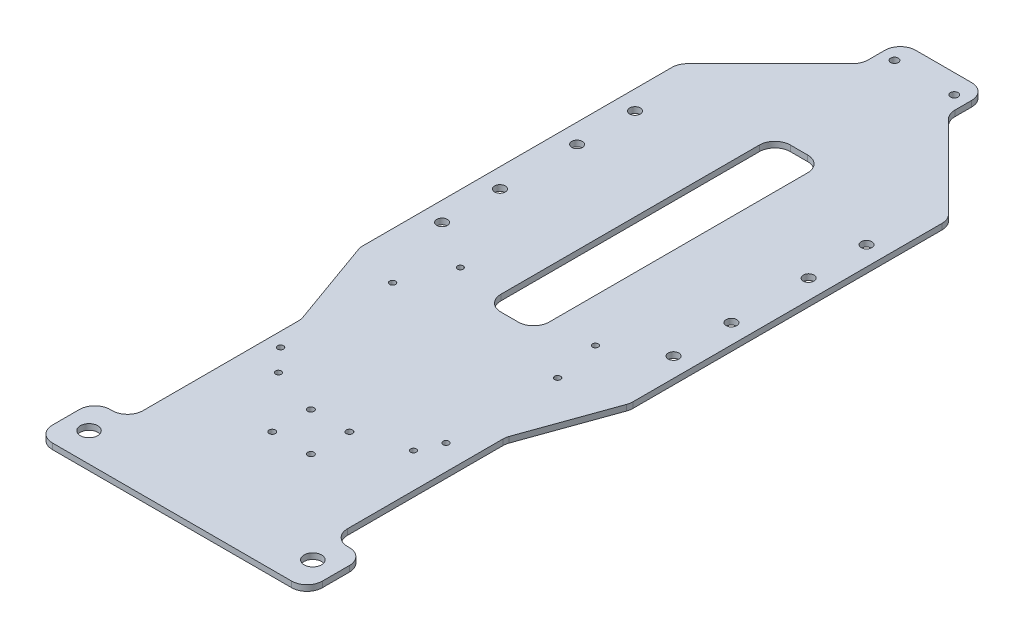
SolidWorks part; units mm, degrees
ref_plane "Front Plane" through (0, 0, 0) normal (0, 0, 1) x (1, 0, 0)
ref_plane "Top Plane" through (0, 0, 0) normal (0, 1, 0) x (1, 0, 0)
ref_plane "Right Plane" through (0, 0, 0) normal (1, 0, 0) x (0, 0, -1)
sketch "Sketch1" plane through (0, 0, 0) normal (0, 1, 0) x (1, 0, 0)
  line L0 (0, 200.8671) -> (139, 200.8671) construction
  line L1 (120.6906, 206.9991) -> (259.6906, 206.9991) construction
  line L2 (47.5, 400) -> (92.5, 400)
  line L3 (140, 332.5) -> (140, 167.5)
  line L4 (140, 167.5) -> (123, 120)
  line L6 (123, 120) -> (123, 30)
  line L7 (140, 30) -> (140, 0)
  line L8 (140, 0) -> (0, 0)
  line L9 (0, 0) -> (0, 30)
  line L10 (0, 167.5) -> (0, 332.5)
  line L12 (123, 30) -> (140, 30)
  line L13 (92.5, 400) -> (92.5, 380)
  line L14 (92.5, 380) -> (140, 332.5)
  line L15 (47.5, 400) -> (47.5, 380)
  line L16 (47.5, 380) -> (0, 332.5)
  line L17 (0, 167.5) -> (17, 120)
  line L19 (17, 120) -> (17, 30)
  line L21 (17, 30) -> (0, 30)
  line L22 (0, 332.5) -> (140, 332.5)
  dimension "D1" = 139
  dimension "D2" = 139
  dimension "D3" = 165
  dimension "D4" = 140
  dimension "D5" = 45
  dimension "D6" = 47.5
  dimension "D7" = 30
  dimension "D8" = 47.5
  dimension "D9" = 20
  dimension "D14" = 200.8671
  dimension "D16" = 206.9991
  dimension "D19" = 90
  dimension "D20" = 17
extrude "Boss-Extrude2" add sketch "Sketch1" along normal blind 3 contours L10 L16 L15 L2 L13 L14 L3 L4 L6 L12 L7 L8 L9 L21 L19 L17
sketch "Sketch2" plane through (0, 3, 0) normal (0, 1, 0) x (1, 0, 0)
  line L0 (128, 15) -> (12, 15) construction
  line L1 (85.5, 390) -> (54.5, 390) construction
  line L2 (70, 390) -> (70, 15) construction
  line L3 (70, 390) -> (70, 400) construction
  line L4 (47.5, 400) -> (92.5, 400) construction
  line L5 (128, 15) -> (140, 15) construction
  line L6 (140, 30) -> (140, 0) construction
  line L7 (57.5, 325) -> (82.5, 175) construction
  line L8 (82.5, 175) -> (57.5, 175)
  line L9 (82.5, 175) -> (82.5, 325)
  line L10 (82.5, 325) -> (57.5, 325)
  line L11 (57.5, 175) -> (57.5, 325)
  line L14 (130, 250) -> (10, 250) construction
  line L19 (10, 200) -> (10, 300) construction
  line L20 (130, 200) -> (130, 300) construction
  line L21 (140, 332.5) -> (140, 167.5) construction
  circle A0 centre (12, 15) radius 4.5
  circle A1 centre (128, 15) radius 4.5
  circle A2 centre (54.5, 390) radius 2
  circle A3 centre (85.5, 390) radius 2
  circle A4 centre (10, 270) radius 2.75
  circle A5 centre (10, 300) radius 2.75
  circle A6 centre (10, 230) radius 2.75
  circle A7 centre (10, 200) radius 2.75
  circle A8 centre (130, 270) radius 2.75
  circle A9 centre (130, 300) radius 2.75
  circle A10 centre (130, 230) radius 2.75
  circle A11 centre (130, 200) radius 2.75
  point P36 (70, 250)
  point P41 (70, 250)
  point P42 (130, 250)
  point P43 (140, 250)
  point P46 (10, 250)
  dimension "D1" = 30
  dimension "D2" = 4
  dimension "D3" = 100
  dimension "D4" = 9
  dimension "D9" = 25
  dimension "D11" = 5.5
  dimension "D5" = 116
  dimension "D6" = 31
  dimension "D7" = 375
  dimension "D8" = 30
  dimension "D10" = 150
  dimension "D13" = 120
extrude "Cut-Extrude1" cut sketch "Sketch2" against normal blind 10
fillet "Fillet1" radius 8 20 edges at (57.5, 1.5, -175) (82.5, 1.5, -175) (82.5, 1.5, -325) (57.5, 1.5, -325) (47.5, 1.5, -400) (92.5, 1.5, -400) (92.5, 1.5, -380) (140, 1.5, -332.5) (140, 1.5, -167.5) (123, 1.5, -120) (0, 1.5, -30) (0, 1.5, 0) (140, 1.5, 0) (140, 1.5, -30) (123, 1.5, -30) (17, 1.5, -30) (17, 1.5, -120) (0, 1.5, -167.5) (0, 1.5, -332.5) (47.5, 1.5, -380)
sketch "Sketch3" plane through (0, 3, 0) normal (0, 1, 0) x (1, 0, 0)
  circle A0 centre (60, 61.9811) radius 1.65 construction
  circle A1 centre (80, 61.9811) radius 1.65 construction
  circle A2 centre (80, 81.9811) radius 1.65 construction
  circle A3 centre (60, 81.9811) radius 1.65 construction
  circle A4 centre (60, 61.9811) radius 1.65
  circle A5 centre (80, 61.9811) radius 1.65
  circle A6 centre (80, 81.9811) radius 1.65
  circle A7 centre (60, 81.9811) radius 1.65
  spline S0 degree 3 poles (106.5, 184.472) (106.5, 187.472) (103.5, 187.472) (103.5, 184.472) (103.5, 181.472) (106.5, 181.472) (106.5, 184.472) (106.5, 187.472) (103.5, 187.472) knots -0.5 0 0 0 0.5 0.5 0.5 1 1 1 1.5 1.5 1.5 weights 1 0.333333 0.333333 1 0.333333 0.333333 1 0.333333 0.333333 only from (106.5, 184.472) to (106.5, 184.472) construction
  spline S1 degree 3 poles (36.5, 184.472) (36.5, 187.472) (33.5, 187.472) (33.5, 184.472) (33.5, 181.472) (36.5, 181.472) (36.5, 184.472) (36.5, 187.472) (33.5, 187.472) knots -0.5 0 0 0 0.5 0.5 0.5 1 1 1 1.5 1.5 1.5 weights 1 0.333333 0.333333 1 0.333333 0.333333 1 0.333333 0.333333 only from (36.5, 184.472) to (36.5, 184.472) construction
  spline S2 degree 3 poles (36.5, 90.1614) (36.5, 93.1614) (33.5, 93.1614) (33.5, 90.1614) (33.5, 87.1614) (36.5, 87.1614) (36.5, 90.1614) (36.5, 93.1614) (33.5, 93.1614) knots -0.5 0 0 0 0.5 0.5 0.5 1 1 1 1.5 1.5 1.5 weights 1 0.333333 0.333333 1 0.333333 0.333333 1 0.333333 0.333333 only from (36.5, 90.1614) to (36.5, 90.1614) construction
  spline S3 degree 3 poles (106.5, 90.1614) (106.5, 93.1614) (103.5, 93.1614) (103.5, 90.1614) (103.5, 87.1614) (106.5, 87.1614) (106.5, 90.1614) (106.5, 93.1614) (103.5, 93.1614) knots -0.5 0 0 0 0.5 0.5 0.5 1 1 1 1.5 1.5 1.5 weights 1 0.333333 0.333333 1 0.333333 0.333333 1 0.333333 0.333333 only from (106.5, 90.1614) to (106.5, 90.1614) construction
  spline S4 degree 3 poles (106.5, 184.472) (106.5, 187.472) (103.5, 187.472) (103.5, 184.472) (103.5, 181.472) (106.5, 181.472) (106.5, 184.472) (106.5, 187.472) (103.5, 187.472) knots -0.5 0 0 0 0.5 0.5 0.5 1 1 1 1.5 1.5 1.5 weights 1 0.333333 0.333333 1 0.333333 0.333333 1 0.333333 0.333333 only from (106.5, 184.472) to (106.5, 184.472)
  spline S5 degree 3 poles (36.5, 184.472) (36.5, 187.472) (33.5, 187.472) (33.5, 184.472) (33.5, 181.472) (36.5, 181.472) (36.5, 184.472) (36.5, 187.472) (33.5, 187.472) knots -0.5 0 0 0 0.5 0.5 0.5 1 1 1 1.5 1.5 1.5 weights 1 0.333333 0.333333 1 0.333333 0.333333 1 0.333333 0.333333 only from (36.5, 184.472) to (36.5, 184.472)
  spline S6 degree 3 poles (36.5, 90.1614) (36.5, 93.1614) (33.5, 93.1614) (33.5, 90.1614) (33.5, 87.1614) (36.5, 87.1614) (36.5, 90.1614) (36.5, 93.1614) (33.5, 93.1614) knots -0.5 0 0 0 0.5 0.5 0.5 1 1 1 1.5 1.5 1.5 weights 1 0.333333 0.333333 1 0.333333 0.333333 1 0.333333 0.333333 only from (36.5, 90.1614) to (36.5, 90.1614)
  spline S7 degree 3 poles (106.5, 90.1614) (106.5, 93.1614) (103.5, 93.1614) (103.5, 90.1614) (103.5, 87.1614) (106.5, 87.1614) (106.5, 90.1614) (106.5, 93.1614) (103.5, 93.1614) knots -0.5 0 0 0 0.5 0.5 0.5 1 1 1 1.5 1.5 1.5 weights 1 0.333333 0.333333 1 0.333333 0.333333 1 0.333333 0.333333 only from (106.5, 90.1614) to (106.5, 90.1614)
extrude "Cut-Extrude2" cut sketch "Sketch3" against normal through all both and the other way through all
hole_wizard "M2.5 Clearance Hole" positions "Sketch4" profile "Sketch5" hole size "M2.5" standard "ANSI Metric" end condition through all
sketch "Sketch4" plane through (-64.3038, -30.85, -517.9258) normal (0, -1, 0) x (-1, 0, 0)
  point P0 (-174.0531, -357.8004)
  point P2 (-88.5837, -357.8445)
  point P4 (-88.5837, -415.9179)
  point P6 (-174.3394, -415.9179)
sketch "Sketch5" plane through (109.7493, -30.85, -160.1253) normal (0.7071, 0, 0.7071) x (0.7071, 0, -0.7071)
  line L0 (0, 0) -> (0, 33.85)
  line L1 (0, 33.85) -> (1.55, 33.85)
  line L2 (1.55, 33.85) -> (1.55, 0)
  line L3 (1.55, 0) -> (0, 0)
  line L4 (0, -6.35) -> (0, 107.95) construction
  dimension "Thru Hole Dia." = 3.1
  dimension "Thru Hole Depth" = 33.85
